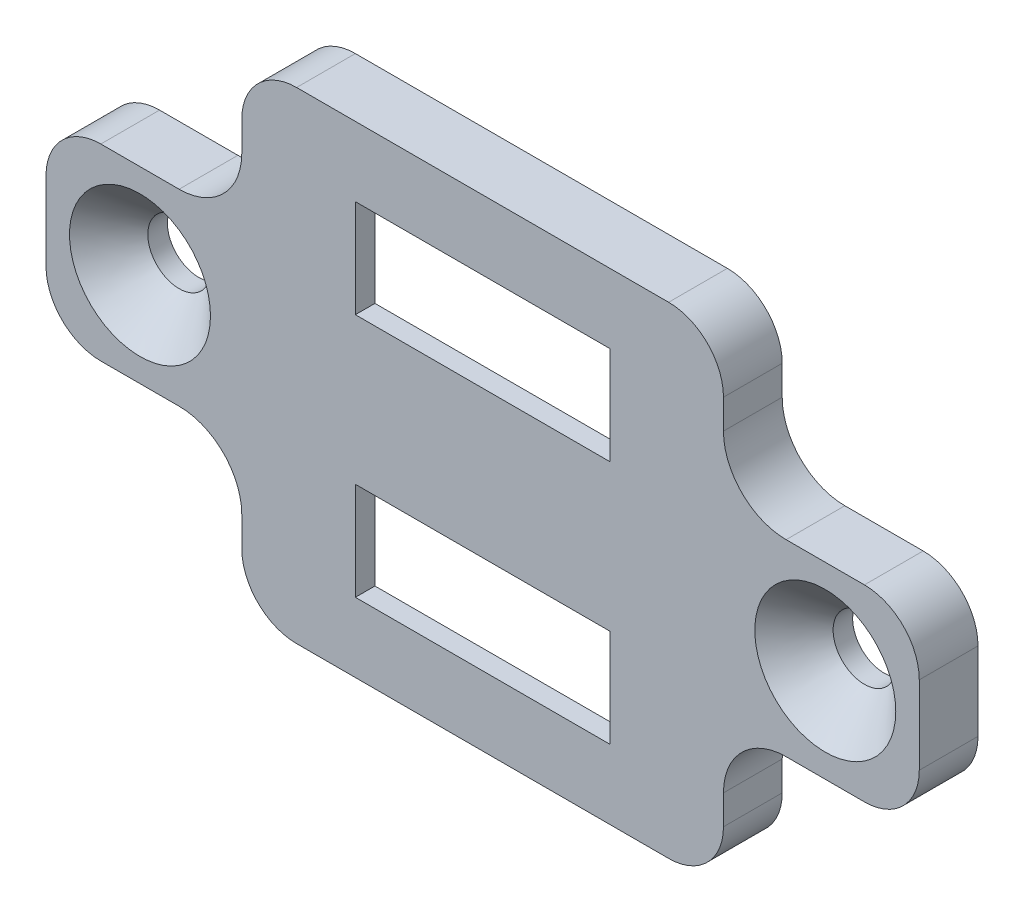
SolidWorks part; units mm, degrees
ref_plane "Plan de face" through (0, 0, 0) normal (0, 0, 1) x (1, 0, 0)
ref_plane "Plan de dessus" through (0, 0, 0) normal (0, 1, 0) x (1, 0, 0)
ref_plane "Plan de droite" through (0, 0, 0) normal (1, 0, 0) x (0, 0, -1)
sketch "Esquisse1" plane through (0, 0, 0) normal (0, 0, 1) x (1, 0, 0)
  line L0 (0, -1000) -> (0, 49000) construction
  line L1 (-9.5, 12.5) -> (9.5, 12.5) construction
  line L2 (-12.5, 9.5) -> (-12.5, 8) construction
  line L3 (-9.5, -12.5) -> (9.5, -12.5) construction
  line L4 (12.5, 9.5) -> (12.5, 8) construction
  line L5 (-12.5, 12.5) -> (12.5, -12.5) construction
  line L6 (-12.5, -12.5) -> (12.5, 12.5) construction
  line L7 (-19.5, 5) -> (-15.5, 5) construction
  line L8 (-22.5, 2) -> (-22.5, -2) construction
  line L9 (-19.5, -5) -> (-15.5, -5) construction
  line L11 (-22.5, 5) -> (-12.5, -5) construction
  line L12 (-22.5, -5) -> (-12.5, 5) construction
  line L13 (22.5, -5) -> (12.5, 5) construction
  line L14 (22.5, 5) -> (12.5, -5) construction
  line L16 (19.5, -5) -> (15.5, -5) construction
  line L17 (22.5, 2) -> (22.5, -2) construction
  line L18 (19.5, 5) -> (15.5, 5) construction
  line L19 (-12.5, -8) -> (-12.5, -9.5) construction
  line L20 (12.5, -8) -> (12.5, -9.5) construction
  line L21 (-9.5, 12.3) -> (9.5, 12.3)
  line L22 (12.3, 9.5) -> (12.3, 8)
  line L23 (19.5, 4.8) -> (15.5, 4.8)
  line L24 (22.3, 2) -> (22.3, -2)
  line L25 (19.5, -4.8) -> (15.5, -4.8)
  line L26 (12.3, -8) -> (12.3, -9.5)
  line L27 (-9.5, -12.3) -> (9.5, -12.3)
  line L28 (-12.3, -8) -> (-12.3, -9.5)
  line L29 (-19.5, -4.8) -> (-15.5, -4.8)
  line L30 (-22.3, 2) -> (-22.3, -2)
  line L31 (-19.5, 4.8) -> (-15.5, 4.8)
  line L32 (-12.3, 9.5) -> (-12.3, 8)
  arc A0 (-15.5, 5) -> (-12.5, 8) centre (-15.5, 8) ccw construction
  arc A1 (-9.5, 12.5) -> (-12.5, 9.5) centre (-9.5, 9.5) ccw construction
  arc A2 (9.5, 12.5) -> (12.5, 9.5) centre (9.5, 9.5) cw construction
  arc A3 (15.5, 5) -> (12.5, 8) centre (15.5, 8) cw construction
  arc A4 (19.5, 5) -> (22.5, 2) centre (19.5, 2) cw construction
  arc A5 (22.5, -2) -> (19.5, -5) centre (19.5, -2) cw construction
  arc A6 (15.5, -5) -> (12.5, -8) centre (15.5, -8) ccw construction
  arc A7 (9.5, -12.5) -> (12.5, -9.5) centre (9.5, -9.5) ccw construction
  arc A8 (-12.5, -9.5) -> (-9.5, -12.5) centre (-9.5, -9.5) ccw construction
  arc A9 (-15.5, -5) -> (-12.5, -8) centre (-15.5, -8) cw construction
  arc A10 (-22.5, -2) -> (-19.5, -5) centre (-19.5, -2) ccw construction
  arc A11 (-19.5, 5) -> (-22.5, 2) centre (-19.5, 2) ccw construction
  arc A12 (9.5, 12.3) -> (12.3, 9.5) centre (9.5, 9.5) cw
  arc A13 (15.5, 4.8) -> (12.3, 8) centre (15.5, 8) cw
  arc A14 (19.5, 4.8) -> (22.3, 2) centre (19.5, 2) cw
  arc A15 (22.3, -2) -> (19.5, -4.8) centre (19.5, -2) cw
  arc A16 (15.5, -4.8) -> (12.3, -8) centre (15.5, -8) ccw
  arc A17 (9.5, -12.3) -> (12.3, -9.5) centre (9.5, -9.5) ccw
  arc A18 (-12.3, -9.5) -> (-9.5, -12.3) centre (-9.5, -9.5) ccw
  arc A19 (-15.5, -4.8) -> (-12.3, -8) centre (-15.5, -8) cw
  arc A20 (-22.3, -2) -> (-19.5, -4.8) centre (-19.5, -2) ccw
  arc A21 (-19.5, 4.8) -> (-22.3, 2) centre (-19.5, 2) ccw
  arc A22 (-15.5, 4.8) -> (-12.3, 8) centre (-15.5, 8) ccw
  arc A23 (-9.5, 12.3) -> (-12.3, 9.5) centre (-9.5, 9.5) ccw
  circle A24 centre (-17.5, 0) radius 1.6
  circle A25 centre (17.5, 0) radius 1.6
  point P0 (0, 0)
  point P7 (-17.5, 0)
  point P17 (17.5, 0)
  dimension "D3" = 3
  dimension "D5" = 3.2
  dimension "D1" = 25
  dimension "D2" = 10
  dimension "D4" = 0.2
extrude "Boss.-Extru.1" add sketch "Esquisse1" along normal blind 3
sketch "Esquisse2" plane through (0, 0, 0) normal (0, 0, -1) x (-1, 0, 0)
  line L1 (-8.75, 11.75) -> (8.75, 11.75)
  line L2 (-11.75, 8.75) -> (-11.75, -8.75)
  line L3 (-8.75, -11.75) -> (8.75, -11.75)
  line L4 (11.75, 8.75) -> (11.75, -8.75)
  line L5 (-11.75, 11.75) -> (11.75, -11.75) construction
  line L6 (-11.75, -11.75) -> (11.75, 11.75) construction
  arc A0 (-11.75, -8.75) -> (-8.75, -11.75) centre (-8.75, -8.75) ccw
  arc A1 (8.75, -11.75) -> (11.75, -8.75) centre (8.75, -8.75) ccw
  arc A2 (8.75, 11.75) -> (11.75, 8.75) centre (8.75, 8.75) cw
  arc A3 (-8.75, 11.75) -> (-11.75, 8.75) centre (-8.75, 8.75) ccw
  point P0 (0, 0)
  dimension "D1" = 3
  dimension "24" = 23.5
extrude "Enlèv. mat.-Extru.1" cut sketch "Esquisse2" against normal blind 2
sketch "Esquisse4" plane through (0, 0, 2) normal (0, 0, -1) x (-1, 0, 0)
  line L0 (8.75, 11.75) -> (-8.75, 11.75) construction
  line L1 (-6.5, 8.75) -> (6.5, 8.75)
  line L2 (-6.5, 8.75) -> (-6.5, 3.75)
  line L3 (-6.5, 3.75) -> (6.5, 3.75)
  line L4 (6.5, 8.75) -> (6.5, 3.75)
  line L5 (-6.5, 8.75) -> (6.5, 3.75) construction
  line L6 (-6.5, 3.75) -> (6.5, 8.75) construction
  line L7 (-1000, 0) -> (49000, 0) construction
  line L8 (-6.5, -3.75) -> (6.5, -3.75)
  line L9 (6.5, -8.75) -> (6.5, -3.75)
  line L10 (-6.5, -8.75) -> (6.5, -8.75)
  line L11 (-6.5, -8.75) -> (-6.5, -3.75)
  point P0 (0, 6.25)
  dimension "D1" = 13
  dimension "D2" = 5
  dimension "D3" = 5.5
extrude "Enlèv. mat.-Extru.2" cut sketch "Esquisse4" against normal through all
chamfer "Chanfrein1" distance 2 angle 45 2 edges at (19.1, 0, 3) (-15.9, 0, 3)
